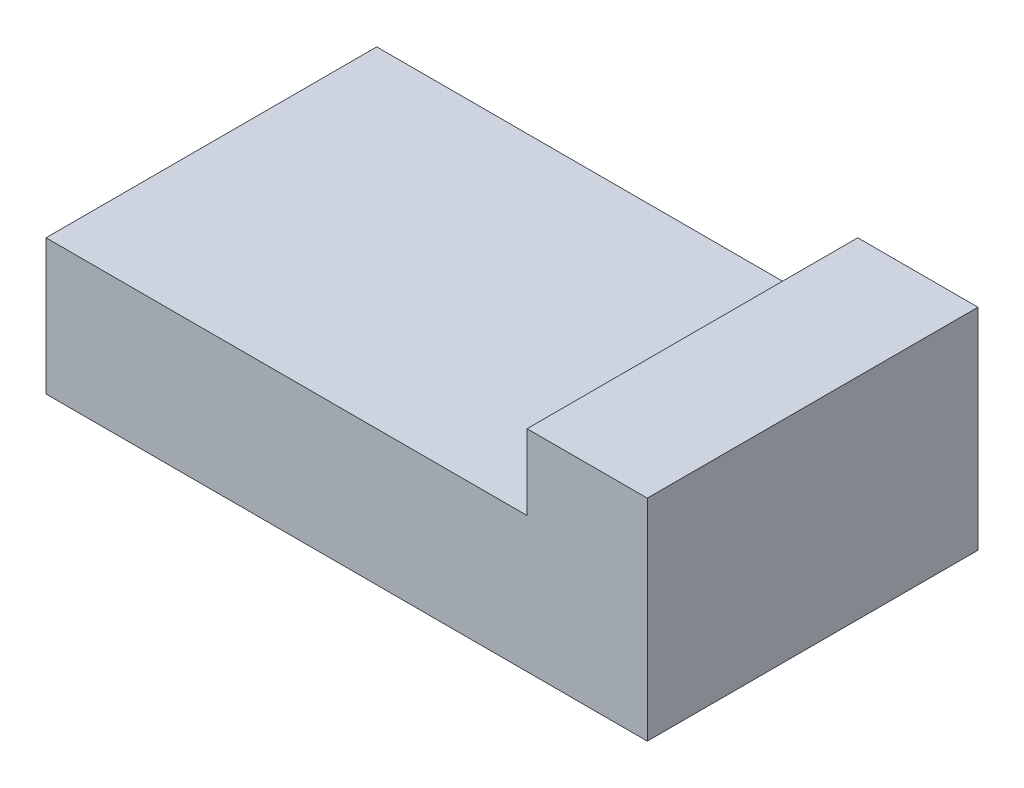
SolidWorks part; units mm, degrees
ref_plane "Спереди" through (0, 0, 0) normal (0, 0, 1) x (1, 0, 0)
ref_plane "Сверху" through (0, 0, 0) normal (0, 1, 0) x (1, 0, 0)
ref_plane "Справа" through (0, 0, 0) normal (1, 0, 0) x (0, 0, -1)
sketch "Эскиз1" plane through (0, 0, 0) normal (0, 1, 0) x (1, 0, 0)
  line L1 (-20, 11) -> (20, 11)
  line L2 (-20, 11) -> (-20, -11)
  line L3 (-20, -11) -> (20, -11)
  line L4 (20, 11) -> (20, -11)
  line L5 (-20, 11) -> (20, -11) construction
  line L6 (-20, -11) -> (20, 11) construction
  point P0 (0, 0)
  dimension "D1" = 22
  dimension "D2" = 40
extrude "Бобышка-Вытянуть1" add sketch "Эскиз1" along normal blind 9
sketch "Эскиз2" plane through (0, 9, 0) normal (0, 1, 0) x (1, 0, 0)
  line L0 (-20, -11) -> (20, -11) construction
  line L1 (20, 11) -> (12, 11)
  line L2 (20, 11) -> (20, -11)
  line L3 (20, -11) -> (12, -11)
  line L4 (12, 11) -> (12, -11)
  dimension "D1" = 8
extrude "Бобышка-Вытянуть2" add sketch "Эскиз2" along normal blind 5
